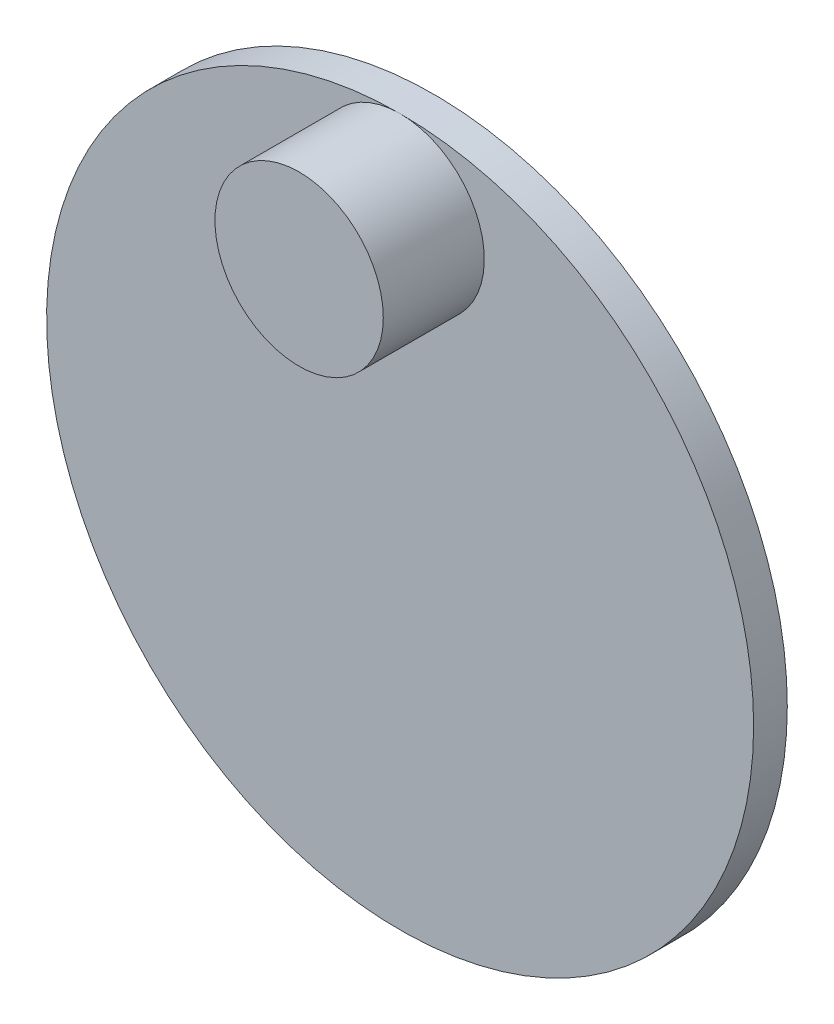
SolidWorks part; units mm, degrees
ref_plane "Front Plane" through (0, 0, 0) normal (0, 0, 1) x (1, 0, 0)
ref_plane "Top Plane" through (0, 0, 0) normal (0, 1, 0) x (1, 0, 0)
ref_plane "Right Plane" through (0, 0, 0) normal (1, 0, 0) x (0, 0, -1)
sketch "Sketch1" plane through (0, 0, 0) normal (0, 0, 1) x (1, 0, 0)
  circle A0 centre (0, 0) radius 115
  dimension "D1" = 230
extrude "Boss-Extrude1" add sketch "Sketch1" along normal blind 10 contours A0
sketch "Sketch2" plane through (0, 0, 10) normal (0, 0, 1) x (1, 0, 0)
  line L0 (0, 0) -> (0, 80) construction
  circle A0 centre (0, 80) radius 25
  dimension "D1" = 80
extrude "Boss-Extrude2" add sketch "Sketch2" along normal blind 30
sketch "Sketch3" plane through (0, 0, 0) normal (0, 0, -1) x (-1, 0, 0)
  circle A0 centre (0, 0) radius 30
  dimension "D1" = 60
extrude "Boss-Extrude3" add sketch "Sketch3" along normal blind 30
sketch "Sketch4" plane through (0, 0, 10) normal (0, 0, 1) x (1, 0, 0)
  circle A0 centre (0, 0) radius 115
  circle A1 centre (0, 0) radius 105
extrude "Cut-Extrude2" cut sketch "Sketch4" against normal blind 10
